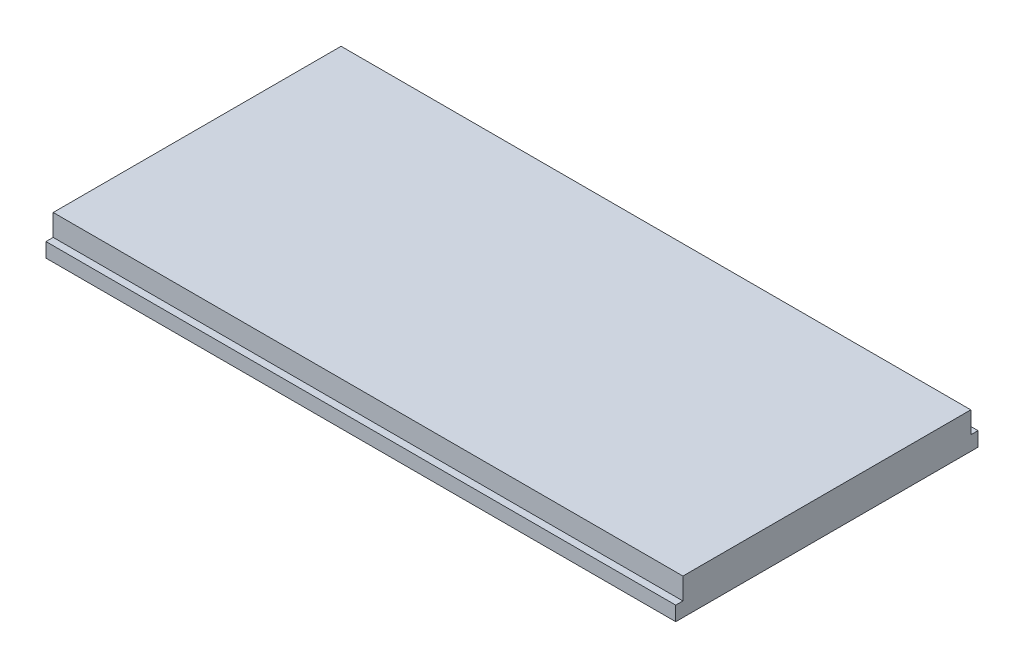
SolidWorks part; units mm, degrees
ref_plane "Front Plane" through (0, 0, 0) normal (0, 0, 1) x (1, 0, 0)
ref_plane "Top Plane" through (0, 0, 0) normal (0, 1, 0) x (1, 0, 0)
ref_plane "Right Plane" through (0, 0, 0) normal (1, 0, 0) x (0, 0, -1)
sketch "Sketch1" plane through (0, 0, 0) normal (0, 1, 0) x (1, 0, 0)
  line L1 (-43.75, 21) -> (43.75, 21)
  line L2 (-43.75, 21) -> (-43.75, -21)
  line L3 (-43.75, -21) -> (43.75, -21)
  line L4 (43.75, 21) -> (43.75, -21)
  line L5 (-43.75, 21) -> (43.75, -21) construction
  line L6 (-43.75, -21) -> (43.75, 21) construction
  point P0 (0, 0)
extrude "Boss-Extrude1" add sketch "Sketch1" along normal blind 5
sketch "Sketch2" plane through (0, 5, 0) normal (0, 1, 0) x (1, 0, 0)
  line L0 (-43.75, 21) -> (-43.75, -21) construction
  line L1 (43.75, 21) -> (-43.75, 21)
  line L2 (43.75, 21) -> (43.75, 20)
  line L3 (43.75, 20) -> (-43.75, 20)
  line L4 (-43.75, 21) -> (-43.75, 20)
extrude "Cut-Extrude1" cut sketch "Sketch2" against normal blind 3
sketch "Sketch3" plane through (0, 5, 0) normal (0, 1, 0) x (1, 0, 0)
  line L0 (43.75, -21) -> (43.75, 20) construction
  line L1 (-43.75, -21) -> (43.75, -21)
  line L2 (-43.75, -21) -> (-43.75, -20)
  line L3 (-43.75, -20) -> (43.75, -20)
  line L4 (43.75, -21) -> (43.75, -20)
extrude "Cut-Extrude2" cut sketch "Sketch3" against normal blind 3
